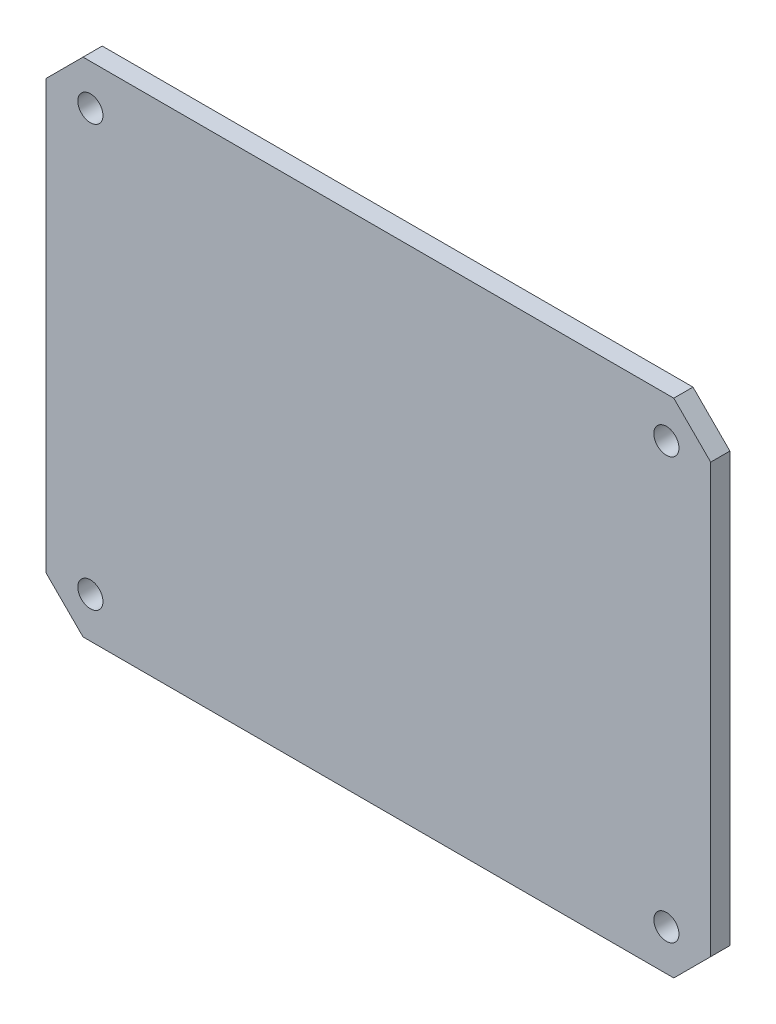
SolidWorks part; units mm, degrees
ref_plane "前视基准面" through (0, 0, 0) normal (0, 0, 1) x (1, 0, 0)
ref_plane "上视基准面" through (0, 0, 0) normal (0, 1, 0) x (1, 0, 0)
ref_plane "右视基准面" through (0, 0, 0) normal (1, 0, 0) x (0, 0, -1)
other "Configuration Table"
sketch "Flat cover with four D3.4 clearances profile" plane through (0, 0, 0) normal (0, 0, 1) x (1, 0, 0)
  line L0 (-40, -34) -> (40, -34)
  line L1 (40, -34) -> (45, -29)
  line L2 (45, -29) -> (45, 29)
  line L3 (45, 29) -> (40, 34)
  line L4 (40, 34) -> (-40, 34)
  line L5 (-40, 34) -> (-45, 29)
  line L6 (-45, 29) -> (-45, -29)
  line L7 (-45, -29) -> (-40, -34)
  circle A0 centre (-39, -28.5) radius 1.7
  circle A1 centre (39, -28.5) radius 1.7
  circle A2 centre (-39, 28.5) radius 1.7
  circle A3 centre (39, 28.5) radius 1.7
extrude "Flat cover with four D3.4 clearances" add sketch "Flat cover with four D3.4 clearances profile" along normal blind 2.6
